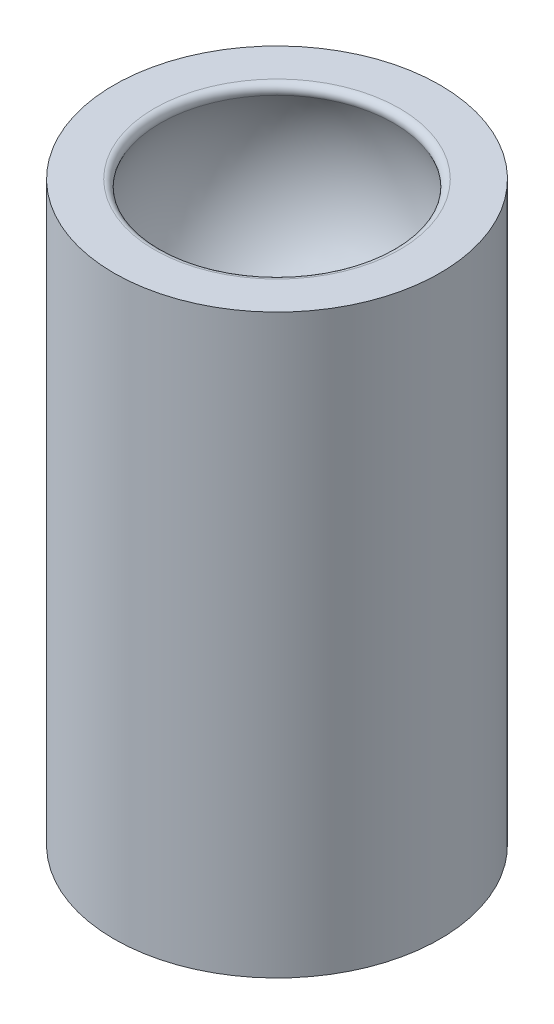
SolidWorks part; units mm, degrees
ref_plane "Front Plane" through (0, 0, 0) normal (0, 0, 1) x (1, 0, 0)
ref_plane "Top Plane" through (0, 0, 0) normal (0, 1, 0) x (1, 0, 0)
ref_plane "Right Plane" through (0, 0, 0) normal (1, 0, 0) x (0, 0, -1)
sketch "Sketch1" plane through (0, 0, 0) normal (0, 1, 0) x (1, 0, 0)
  circle A0 centre (0, 0) radius 2.375
  circle A1 centre (0, 0) radius 4.875
  dimension "D1" = 4.75
  dimension "D3" = 9.75
  dimension "D2" = 2.5
extrude "Boss-Extrude1" add sketch "Sketch1" along normal blind 17.25 contours A1 A0
ref_plane "Plane1" through (0, 15, 0) normal (0, -1, 0) x (-1, 0, 0)
sketch "Sketch3" plane through (0, 15, 0) normal (0, -1, 0) x (-1, 0, 0)
  line L0 (0, 4) -> (0, -4)
  line L1 (0, 5.1477) -> (0, -5.2038) construction
  arc A0 (0, 4) -> (0, -4) centre (0, 0) cw
  dimension "D1" = 4
revolve "Cut-Revolve3" cut sketch "Sketch3" angle 360 about L1
fillet "Fillet1" radius 0.2 1 edges at (0, 17.25, 3.3072)
